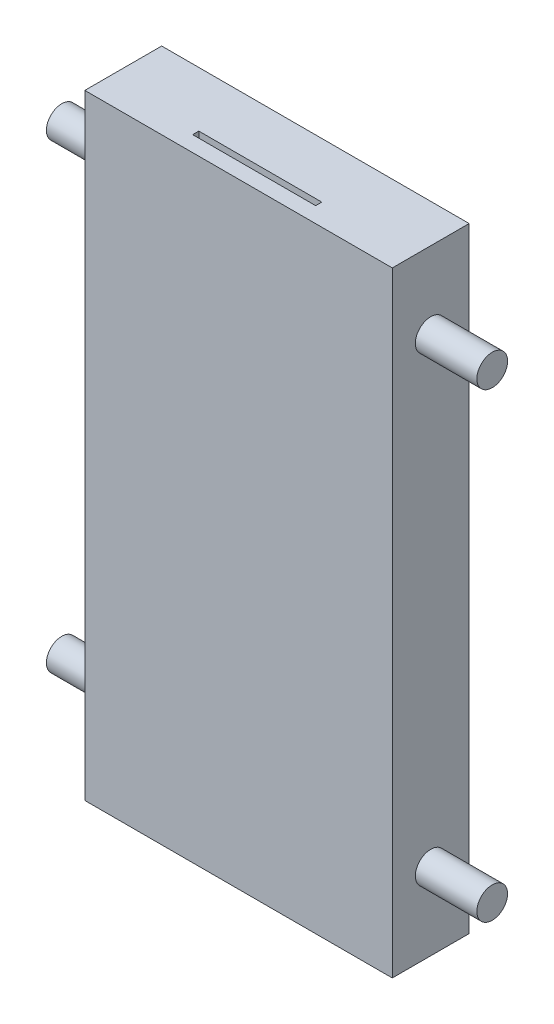
SolidWorks part; units mm, degrees
ref_plane "Front Plane" through (0, 0, 0) normal (0, 0, 1) x (1, 0, 0)
ref_plane "Top Plane" through (0, 0, 0) normal (0, 1, 0) x (1, 0, 0)
ref_plane "Right Plane" through (0, 0, 0) normal (1, 0, 0) x (0, 0, -1)
sketch "Sketch1" plane through (0, 0, 0) normal (0, 0, 1) x (1, 0, 0)
  line L0 (0, 0) -> (0, 25.4)
  line L1 (0, 25.4) -> (12.7, 25.4)
  line L2 (12.7, 25.4) -> (12.7, 0)
  line L3 (12.7, 0) -> (0, 0)
  dimension "D1" = 12.7
  dimension "D2" = 25.4
extrude "Boss-Extrude1" add sketch "Sketch1" along normal blind 3.175
sketch "Sketch2" plane through (12.7, 0, 0) normal (1, 0, 0) x (0, 0, -1)
  line L0 (-1.5875, 25.4) -> (-1.5875, 22.225)
  line L1 (-3.175, 25.4) -> (0, 25.4) construction
  circle A0 centre (-1.5875, 22.225) radius 0.635
  dimension "D2" = 1.27
  dimension "D1" = 3.175
extrude "Boss-Extrude3" add sketch "Sketch2" along normal blind 2.54 and the other way blind 15.24
sketch "Sketch5" plane through (12.7, 0, 0) normal (1, 0, 0) x (0, 0, -1)
  line L1 (-3.175, 0) -> (0, 0) construction
  circle A0 centre (-1.2538, 3.175) radius 0.254
  dimension "D1" = 0.508
  dimension "D2" = 3.175
sketch "Sketch6" plane through (12.7, 0, 0) normal (1, 0, 0) x (0, 0, -1)
  line L0 (-3.175, 0) -> (0, 0) construction
  circle A0 centre (-1.5875, 3.175) radius 0.635
  dimension "D1" = 1.27
  dimension "D2" = 3.175
extrude "Boss-Extrude5" add sketch "Sketch6" along normal blind 2.54 and the other way blind 15.24
sketch "Sketch7" plane through (0, 25.4, 0) normal (0, 1, 0) x (1, 0, 0)
  line L0 (6.35, -3.175) -> (6.35, -0.7313) construction
  line L1 (12.7, -3.175) -> (0, -3.175) construction
  line L3 (8.89, -2.5306) -> (3.81, -2.5306)
  line L4 (8.89, -2.5306) -> (8.89, -2.2766)
  line L5 (8.89, -2.2766) -> (3.81, -2.2766)
  line L6 (3.81, -2.5306) -> (3.81, -2.2766)
  line L7 (8.89, -2.5306) -> (3.81, -2.2766) construction
  line L8 (8.89, -2.2766) -> (3.81, -2.5306) construction
  point P4 (6.35, -2.4036)
  dimension "D1" = 5.08
  dimension "D2" = 0.254
extrude "Cut-Extrude1" cut sketch "Sketch7" against normal through all
